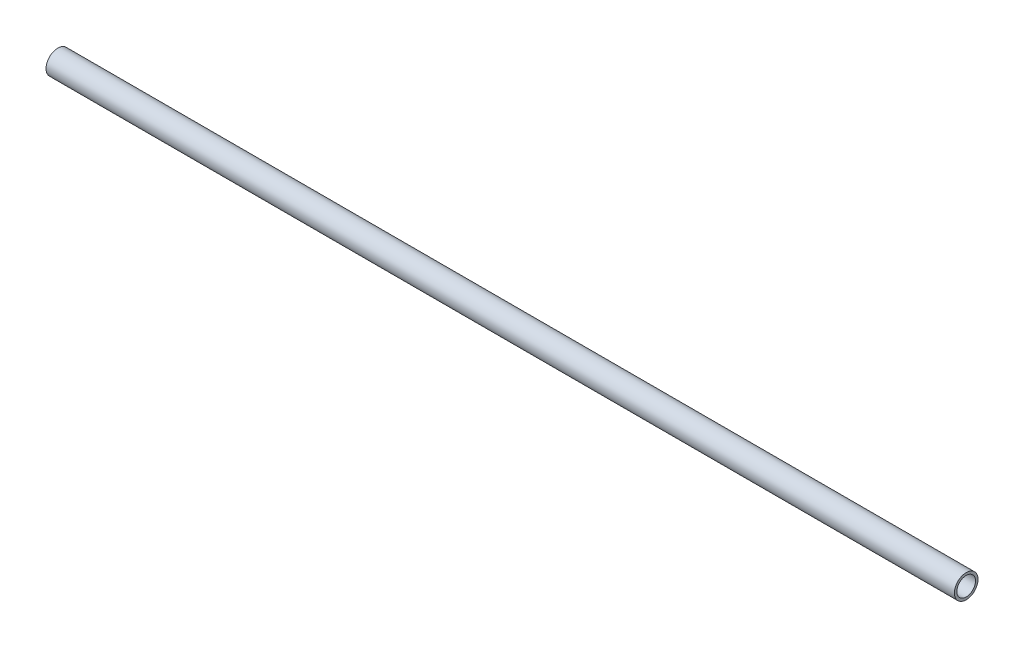
SolidWorks part; units mm, degrees
ref_plane "Alzado" through (0, 0, 0) normal (0, 0, 1) x (1, 0, 0)
ref_plane "Planta" through (0, 0, 0) normal (0, 1, 0) x (1, 0, 0)
ref_plane "Vista lateral" through (0, 0, 0) normal (1, 0, 0) x (0, 0, -1)
sketch "Croquis1" plane through (0, 0, 0) normal (1, 0, 0) x (0, 0, -1)
  circle A0 centre (0, 0) radius 19
  circle A1 centre (0, 0) radius 15
extrude "Saliente-Extruir1" add sketch "Croquis1" along normal blind 1460
